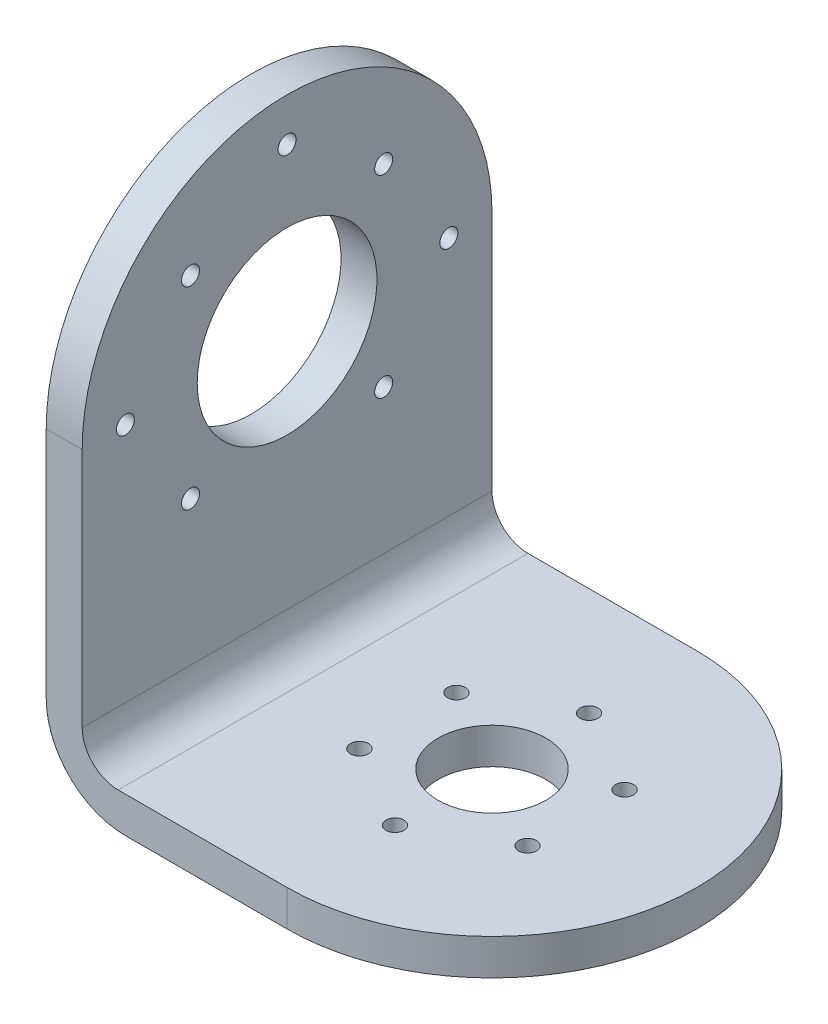
SolidWorks part; units mm, degrees
material "AISI 304"
ref_plane "前视基准面" through (0, 0, 0) normal (0, 0, 1) x (1, 0, 0)
ref_plane "上视基准面" through (0, 0, 0) normal (0, 1, 0) x (1, 0, 0)
ref_plane "右视基准面" through (0, 0, 0) normal (1, 0, 0) x (0, 0, -1)
other "Configuration Table"
sketch "草图1" plane through (0, 0, 0) normal (0, 0, 1) x (1, 0, 0)
  line L0 (0, 0) -> (0, 72)
  line L1 (0, 72) -> (5, 72)
  line L2 (5, 72) -> (5, 5)
  line L3 (5, 5) -> (62, 5)
  line L4 (62, 5) -> (62, 0)
  line L5 (62, 0) -> (0, 0)
  dimension "D1" = 5
  dimension "D2" = 5
  dimension "D3" = 62
  dimension "D4" = 72
extrude "凸台-拉伸1" add sketch "草图1" along normal blind 57
sketch "草图2" plane through (0, 0, 0) normal (-1, 0, 0) x (0, 0, 1)
  line L1 (57, 72) -> (0, 72) construction
  line L2 (0, 72) -> (0, 0) construction
  line L3 (57, 72) -> (57, 0) construction
  line L4 (57, 72) -> (57, 0)
  line L5 (0, 72) -> (0, 0)
  line L6 (57, 72) -> (0, 72)
  circle A0 centre (28.5, 43.5) radius 28.5
  dimension "D1" = 57
extrude "切除-拉伸1" cut sketch "草图2" against normal blind 57 contours A0 L6 L1 | A0 L4
sketch "草图3" plane through (0, 0, 0) normal (0, -1, 0) x (1, 0, 0)
  line L0 (0, 57) -> (62, 57) construction
  line L1 (62, 57) -> (62, 0) construction
  line L2 (0, 0) -> (62, 0) construction
  line L3 (0, 0) -> (62, 0)
  line L4 (0, 57) -> (62, 57)
  line L5 (62, 57) -> (62, 0)
  circle A0 centre (33.5, 28.5) radius 28.5
  line M3 (62, 0) -> (62, 57)
  line M4 (62, 57) -> (0, 57)
  dimension "D1" = 57
extrude "切除-拉伸2" cut sketch "草图3" against normal blind 57 contours A0 L5 M4 | A0 L3 M3
fillet "圆角3" radius 11 1 edges at (0, 0, 28.5)
fillet "圆角4" radius 5 1 edges at (5, 5, 28.5)
sketch "草图4" plane through (0, 0, 0) normal (-1, 0, 0) x (0, 0, 1)
  line L0 (0, 43.5) -> (57, 43.5) construction
  line L1 (28.5, 72) -> (28.5, 5.1894) construction
  line L2 (28.5, 43.5) -> (56.562, 71.562) construction
  arc A0 (57, 43.5) -> (0, 43.5) centre (28.5, 43.5) ccw construction
  circle A1 centre (28.5, 43.5) radius 12.5
  circle A2 centre (41.935, 56.935) radius 1.25
  dimension "D1" = 25
  dimension "D3" = 2.5
  dimension "D2" = 45
  dimension "D4" = 19
extrude "切除-拉伸3" cut sketch "草图4" against normal blind 57
pattern_circular "阵列(圆周)1" count 4 over 360 about axis through (0, 43.5, 28.5) along (1, 0, 0) of "切除-拉伸3"
sketch "草图5" plane through (0, 0, 0) normal (-1, 0, 0) x (0, 0, 1)
  line L0 (0, 43.5) -> (57, 43.5) construction
  circle A0 centre (51, 43.5) radius 1.25
  point P6 (28.5, 43.5)
  dimension "D1" = 2.5
  dimension "D2" = 22.5
extrude "切除-拉伸4" cut sketch "草图5" against normal blind 57
pattern_circular "阵列(圆周)2" count 3 over 180 about axis through (0, 43.5, 28.5) along (1, 0, 0) of "切除-拉伸4"
sketch "草图7" plane through (0, 0, 0) normal (0, -1, 0) x (1, 0, 0)
sketch "草图8" plane through (0, 0, 0) normal (0, -1, 0) x (1, 0, 0)
  line L0 (33.5, 57) -> (33.5, 0) construction
  line L1 (11, 57) -> (33.5, 57) construction
  line L2 (11, 0) -> (33.5, 0) construction
  line L3 (62, 28.5) -> (5.4867, 28.5) construction
  arc A0 (33.5, 0) -> (33.5, 57) centre (33.5, 28.5) ccw construction
  circle A1 centre (33.5, 28.5) radius 7.5
  circle A2 centre (33.5, 15) radius 1.25
  dimension "D1" = 15
  dimension "D2" = 2.5
  dimension "D3" = 13.5
extrude "切除-拉伸6" cut sketch "草图8" against normal blind 57
pattern_circular "阵列(圆周)3" count 6 over 360 about axis through (33.5, 0, 28.5) along (0, 1, 0) of "切除-拉伸6"
